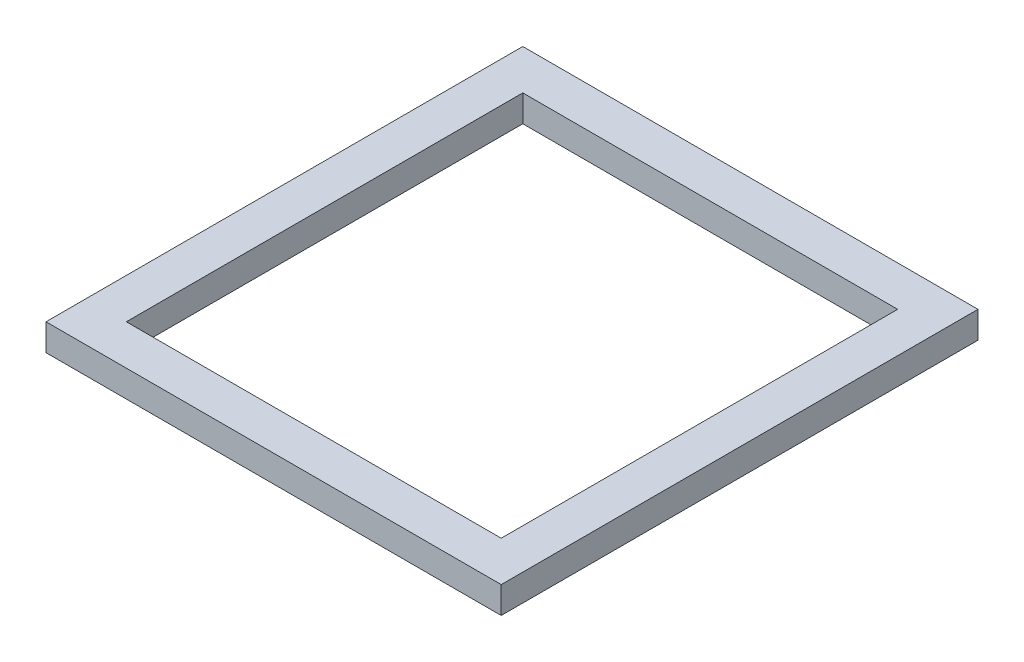
SolidWorks part; units mm, degrees
material "Silicon Rubber"
ref_plane "Front Plane" through (0, 0, 0) normal (0, 0, 1) x (1, 0, 0)
ref_plane "Top Plane" through (0, 0, 0) normal (0, 1, 0) x (1, 0, 0)
ref_plane "Right Plane" through (0, 0, 0) normal (1, 0, 0) x (0, 0, -1)
sketch "Sketch1" plane through (0, 0, 0) normal (0, 1, 0) x (1, 0, 0)
  line L0 (2.3813, 25.8863) -> (24.6062, 25.8863)
  line L1 (0, 0) -> (26.9875, 0)
  line L2 (0, 0) -> (0, 28.2675)
  line L3 (0, 28.2675) -> (26.9875, 28.2675)
  line L4 (26.9875, 0) -> (26.9875, 28.2675)
  line L9 (24.6062, 2.3813) -> (24.6062, 25.8863)
  line L10 (2.3813, 2.3813) -> (24.6062, 2.3813)
  line L11 (2.3813, 2.3813) -> (2.3813, 25.8863)
  dimension "D1" = 2.3813
  dimension "D5" = 26.9875
  dimension "D6" = 28.2675
extrude "Boss-Extrude1" add sketch "Sketch1" along normal blind 1.5875
